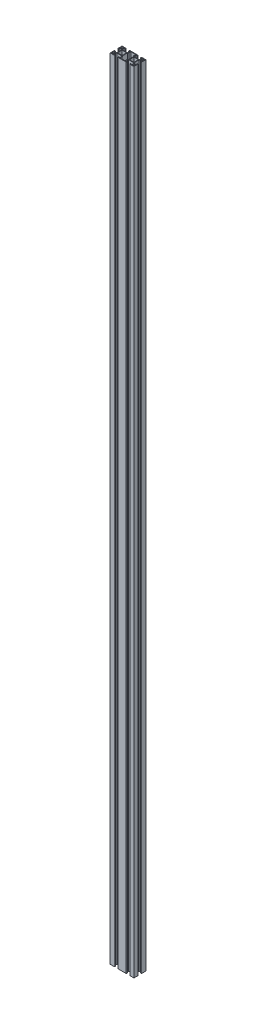
SolidWorks part; units mm, degrees
material "Простая углеродистая сталь"
ref_plane "Спереди" through (0, 0, 0) normal (0, 0, 1) x (1, 0, 0)
ref_plane "Сверху" through (0, 0, 0) normal (0, 1, 0) x (1, 0, 0)
ref_plane "Справа" through (0, 0, 0) normal (1, 0, 0) x (0, 0, -1)
sketch "Эскиз1" plane through (0, 0, 0) normal (0, 1, 0) x (1, 0, 0)
  line L0 (-258.3419, 0) -> (12658.7539, 0) construction
  line L1 (0, -258.3419) -> (0, 12658.7539) construction
  line L2 (15, -258.3419) -> (15, 12658.7539) construction
  line L3 (-15, -258.3419) -> (-15, 12658.7539) construction
  line L4 (22, 7) -> (8, 7)
  line L5 (-30, -15) -> (30, -15)
  line L6 (-30, -15) -> (-30, 15)
  line L7 (-30, 15) -> (30, 15)
  line L8 (30, -15) -> (30, 15)
  line L9 (-30, -15) -> (30, 15) construction
  line L10 (-30, 15) -> (30, -15) construction
  line L11 (-22, -7) -> (-8, -7)
  line L12 (-22, -7) -> (-22, 7)
  line L13 (-22, 7) -> (-8, 7)
  line L14 (-8, -7) -> (-8, 7)
  line L15 (-22, -7) -> (-8, 7) construction
  line L16 (-22, 7) -> (-8, -7) construction
  line L17 (8, -7) -> (8, 7)
  line L18 (22, -7) -> (8, -7)
  line L19 (22, -7) -> (22, 7)
  line L20 (-22, -7) -> (-30, -15) construction
  line L21 (-22, 7) -> (-30, 15) construction
  line L22 (22, 7) -> (30, 15) construction
  line L23 (22, -7) -> (30, -15) construction
  line L24 (24, 9) -> (28.6, 9)
  line L25 (-24, 13.6) -> (-28.6, 13.6)
  line L26 (-24, 13.6) -> (-24, 9)
  line L27 (-24, 9) -> (-28.6, 9)
  line L28 (-28.6, 13.6) -> (-28.6, 9)
  line L29 (-24, 13.6) -> (-28.6, 9) construction
  line L30 (-24, 9) -> (-28.6, 13.6) construction
  line L31 (28.6, 13.6) -> (28.6, 9)
  line L32 (24, 13.6) -> (28.6, 13.6)
  line L33 (24, 13.6) -> (24, 9)
  line L34 (-24, -9) -> (-28.6, -9)
  line L35 (-28.6, -13.6) -> (-28.6, -9)
  line L36 (-24, -13.6) -> (-28.6, -13.6)
  line L37 (-24, -13.6) -> (-24, -9)
  line L38 (24, -13.6) -> (24, -9)
  line L39 (24, -13.6) -> (28.6, -13.6)
  line L40 (28.6, -13.6) -> (28.6, -9)
  line L41 (24, -9) -> (28.6, -9)
  line L42 (-28.4, 8) -> (-23.8485, 8)
  line L43 (-23.8485, 8) -> (-22, 6.1515)
  line L44 (-28.4, 8) -> (-28.4, 6.1)
  line L45 (-28.4, 6.1) -> (-27.8, 6.1)
  line L46 (-27.8, 6.1) -> (-27.8, 4.1)
  line L47 (-27.8, 4.1) -> (-29.2, 4.1)
  line L48 (-29.2, 4.1) -> (-29.2, 4.6)
  line L49 (-29.2, -4.1) -> (-29.2, -4.6)
  line L50 (-30, 4.6) -> (-29.2, 4.6)
  line L51 (-30, -4.6) -> (-29.2, -4.6)
  line L52 (-27.8, -4.1) -> (-29.2, -4.1)
  line L53 (-28.4, -6.1) -> (-27.8, -6.1)
  line L54 (-27.8, -6.1) -> (-27.8, -4.1)
  line L55 (-28.4, -8) -> (-28.4, -6.1)
  line L56 (-28.4, -8) -> (-23.8485, -8)
  line L57 (-23.8485, -8) -> (-22, -6.1515)
  line L58 (-19.6, 15) -> (-19.6, 14.2)
  line L59 (-19.1, 14.2) -> (-19.6, 14.2)
  line L60 (-19.1, 12.8) -> (-19.1, 14.2)
  line L61 (-21.1, 12.8) -> (-19.1, 12.8)
  line L62 (-21.1, 13.4) -> (-21.1, 12.8)
  line L63 (-23, 13.4) -> (-21.1, 13.4)
  line L64 (-23, 13.4) -> (-23, 8.8485)
  line L65 (-23, 8.8485) -> (-21.1515, 7)
  line L66 (-10.4, 15) -> (-10.4, 14.2)
  line L67 (-10.9, 14.2) -> (-10.4, 14.2)
  line L68 (-10.9, 12.8) -> (-10.9, 14.2)
  line L69 (-8.9, 12.8) -> (-10.9, 12.8)
  line L70 (-8.9, 13.4) -> (-8.9, 12.8)
  line L71 (-7, 13.4) -> (-8.9, 13.4)
  line L72 (-6, 13.6) -> (-6, 8.1515)
  line L73 (-7, 13.4) -> (-7, 8.8485)
  line L74 (-7, 8.8485) -> (-8.8485, 7)
  line L75 (-6, 13.6) -> (6, 13.6)
  line L76 (-6, 8.1515) -> (-8, 6.1515)
  line L77 (-10.9, 12.8) -> (-10.9, 14.2)
  line L78 (-10.9, 14.2) -> (-10.4, 14.2)
  line L79 (-10.4, 15) -> (-10.4, 14.2)
  line L80 (-8.9, 13.4) -> (-8.9, 12.8)
  line L81 (-8.9, 12.8) -> (-10.9, 12.8)
  line L82 (-7, 8.8485) -> (-8.8485, 7)
  line L83 (-7, 13.4) -> (-7, 8.8485)
  line L84 (-7, 13.4) -> (-8.9, 13.4)
  line L85 (-21.1, 13.4) -> (-21.1, 12.8)
  line L86 (-21.1, 12.8) -> (-19.1, 12.8)
  line L87 (-19.1, 14.2) -> (-19.6, 14.2)
  line L88 (-19.1, 12.8) -> (-19.1, 14.2)
  line L89 (-19.6, 15) -> (-19.6, 14.2)
  line L90 (-23, 13.4) -> (-21.1, 13.4)
  line L91 (-23, 13.4) -> (-23, 8.8485)
  line L92 (-23, 8.8485) -> (-21.1515, 7)
  line L93 (-24, 8.1515) -> (-22, 6.1515)
  line L94 (-24, 13.6) -> (-24, 8.1515)
  line L95 (-24, 13.6) -> (-30, 13.6)
  line L96 (-19.1, -14.2) -> (-19.6, -14.2)
  line L97 (-19.6, -15) -> (-19.6, -14.2)
  line L98 (-19.1, -12.8) -> (-19.1, -14.2)
  line L99 (-21.1, -12.8) -> (-19.1, -12.8)
  line L100 (-21.1, -13.4) -> (-21.1, -12.8)
  line L101 (-23, -13.4) -> (-21.1, -13.4)
  line L102 (-23, -13.4) -> (-23, -8.8485)
  line L103 (-23, -8.8485) -> (-21.1515, -7)
  line L104 (-6, -8.1515) -> (-8, -6.1515)
  line L105 (-7, -8.8485) -> (-8.8485, -7)
  line L106 (-10.4, -15) -> (-10.4, -14.2)
  line L107 (-10.9, -14.2) -> (-10.4, -14.2)
  line L108 (-10.9, -12.8) -> (-10.9, -14.2)
  line L109 (-8.9, -13.4) -> (-8.9, -12.8)
  line L110 (-8.9, -12.8) -> (-10.9, -12.8)
  line L111 (-7, -13.4) -> (-8.9, -13.4)
  line L112 (-7, -13.4) -> (-7, -8.8485)
  line L113 (-6, -13.6) -> (-6, -8.1515)
  line L114 (-6, -13.6) -> (6, -13.6)
  line L115 (10.9, 12.8) -> (10.9, 14.2)
  line L116 (-20.8, -5.8) -> (-9.2, -5.8)
  line L117 (-20.8, -5.8) -> (-20.8, 5.8)
  line L118 (-20.8, 5.8) -> (-9.2, 5.8)
  line L119 (-9.2, -5.8) -> (-9.2, 5.8)
  line L120 (-20.8, -5.8) -> (-9.2, 5.8) construction
  line L121 (-20.8, 5.8) -> (-9.2, -5.8) construction
  line L122 (10.9, 14.2) -> (10.4, 14.2)
  line L123 (10.4, 15) -> (10.4, 14.2)
  line L124 (7, 13.4) -> (8.9, 13.4)
  line L125 (8.9, 13.4) -> (8.9, 12.8)
  line L126 (8.9, 12.8) -> (10.9, 12.8)
  line L127 (6, 8.1515) -> (8, 6.1515)
  line L128 (7, 8.8485) -> (8.8485, 7)
  line L129 (7, 13.4) -> (7, 8.8485)
  line L130 (6, 13.6) -> (6, 8.1515)
  line L131 (19.6, 15) -> (19.6, 14.2)
  line L132 (19.1, 14.2) -> (19.6, 14.2)
  line L133 (19.1, 12.8) -> (19.1, 14.2)
  line L134 (21.1, 13.4) -> (21.1, 12.8)
  line L135 (21.1, 12.8) -> (19.1, 12.8)
  line L136 (23, 13.4) -> (21.1, 13.4)
  line L137 (23, 13.4) -> (23, 8.8485)
  line L138 (23, 8.8485) -> (21.1515, 7)
  line L139 (23.8485, 8) -> (22, 6.1515)
  line L140 (28.4, 8) -> (23.8485, 8)
  line L141 (28.4, 8) -> (28.4, 6.1)
  line L142 (28.4, 6.1) -> (27.8, 6.1)
  line L143 (27.8, 6.1) -> (27.8, 4.1)
  line L144 (29.2, 4.1) -> (29.2, 4.6)
  line L145 (27.8, 4.1) -> (29.2, 4.1)
  line L146 (30, 4.6) -> (29.2, 4.6)
  line L147 (23, -8.8485) -> (21.1515, -7)
  line L148 (23.8485, -8) -> (22, -6.1515)
  line L149 (28.4, -8) -> (23.8485, -8)
  line L150 (28.4, -8) -> (28.4, -6.1)
  line L151 (28.4, -6.1) -> (27.8, -6.1)
  line L152 (30, -4.6) -> (29.2, -4.6)
  line L153 (27.8, -6.1) -> (27.8, -4.1)
  line L154 (27.8, -4.1) -> (29.2, -4.1)
  line L155 (29.2, -4.1) -> (29.2, -4.6)
  line L156 (20.8, 5.8) -> (9.2, 5.8)
  line L157 (9.2, -5.8) -> (9.2, 5.8)
  line L158 (20.8, -5.8) -> (9.2, -5.8)
  line L159 (20.8, -5.8) -> (20.8, 5.8)
  line L160 (19.6, -15) -> (19.6, -14.2)
  line L161 (19.1, -14.2) -> (19.6, -14.2)
  line L162 (19.1, -12.8) -> (19.1, -14.2)
  line L163 (21.1, -13.4) -> (21.1, -12.8)
  line L164 (21.1, -12.8) -> (19.1, -12.8)
  line L165 (23, -13.4) -> (23, -8.8485)
  line L166 (23, -13.4) -> (21.1, -13.4)
  line L167 (10.4, -15) -> (10.4, -14.2)
  line L168 (10.9, -14.2) -> (10.4, -14.2)
  line L169 (10.9, -12.8) -> (10.9, -14.2)
  line L170 (8.9, -12.8) -> (10.9, -12.8)
  line L171 (8.9, -13.4) -> (8.9, -12.8)
  line L172 (7, -13.4) -> (8.9, -13.4)
  line L173 (6, -13.6) -> (6, -8.1515)
  line L174 (7, -13.4) -> (7, -8.8485)
  line L175 (7, -8.8485) -> (8.8485, -7)
  line L176 (6, -8.1515) -> (8, -6.1515)
  point P9 (0, 0)
  point P14 (-15, 0)
  point P23 (-26.3, 11.3)
  point P105 (-15, 0)
  point P121 (0, 13.6)
  point P169 (0, -13.6)
  dimension "D1" = 15
  dimension "D2" = 60
  dimension "D3" = 30
  dimension "D4" = 8
  dimension "D5" = 8
  dimension "D6" = 1.4
  dimension "D7" = 4.6
  dimension "D8" = 4.1
  dimension "D9" = 4.6
  dimension "D10" = 2.2
  dimension "D11" = 1.6
  dimension "D12" = 0.6
  dimension "D13" = 0.8
  dimension "D14" = 2
  dimension "D15" = 1.2
extrude "Бобышка-Вытянуть2" add sketch "Эскиз1" along normal blind 2000 contours L176 L173 L114 L113 L104 L14 L11 L105 L112 L111 L109 L110 L108 L107 L106 L5 L167 L168 L169 L170 L171 L172 L174 L175 L18 L17 | L11 L14 L13 L12 L119 L116 L117 L118 | L102 L103 L11 L12 L57 L56 L55 L53 L54 L52 L49 L51 L6 L5 L97 L96 L98 L99 L100 L101 L37 L36 L35 L34 | L18 L19 L4 L17 L159 L158 L157 L156 | L165 L166 L163 L164 L162 L161 L160 L5 L8 L152 L155 L154 L153 L151 L150 L149 L148 L19 L18 L147 L38 L41 L40 L39 | L146 L8 L7 L131 L132 L133 L135 L134 L136 L137 L138 L4 L19 L139 L140 L141 L142 L143 L145 L144 L33 L32 L31 L24 | L75 L130 L127 L17 L4 L128 L129 L124 L125 L126 L115 L122 L123 L7 L66 L67 L68 L69 L70 L71 L73 L74 L13 L14 L76 L72 | L95 L25 L26 L94 L93 L43 L12 L13 L65 L64 L63 L62 L61 L60 L59 L58 L7 L6 | L28 L95 L6 L50 L48 L47 L46 L45 L44 L42 L93 L94 L27
